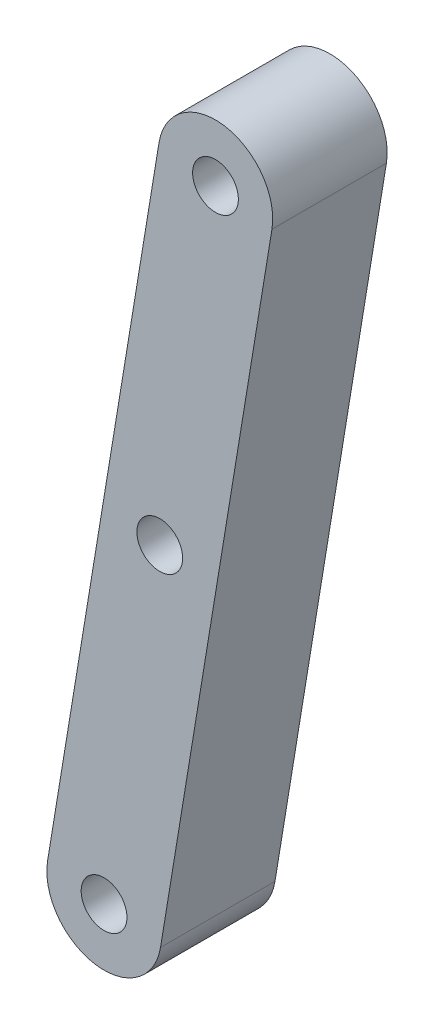
SolidWorks part; units mm, degrees
ref_plane "Front Plane" through (0, 0, 0) normal (0, 0, 1) x (1, 0, 0)
ref_plane "Top Plane" through (0, 0, 0) normal (0, 1, 0) x (1, 0, 0)
ref_plane "Right Plane" through (0, 0, 0) normal (1, 0, 0) x (0, 0, -1)
sketch "Sketch1" plane through (0, 0, 0) normal (0, 0, 1) x (1, 0, 0)
  line L16 (-5.1995, 20.0163) -> (-14.9338, -39.1888)
  line L44 (-5.0662, -40.8112) -> (4.6681, 18.3939)
  circle A4 centre (-10, -40) radius 2
  circle A5 centre (-5.1329, -10.3975) radius 2
  circle A6 centre (-0.2657, 19.2051) radius 2
  arc A7 (-14.9338, -39.1888) -> (-5.0662, -40.8112) centre (-10, -40) ccw
  arc A8 (4.6681, 18.3939) -> (-5.1995, 20.0163) centre (-0.2657, 19.2051) ccw
  dimension "D5" = 60
extrude "Boss-Extrude1" add sketch "Sketch1" along normal blind 10
